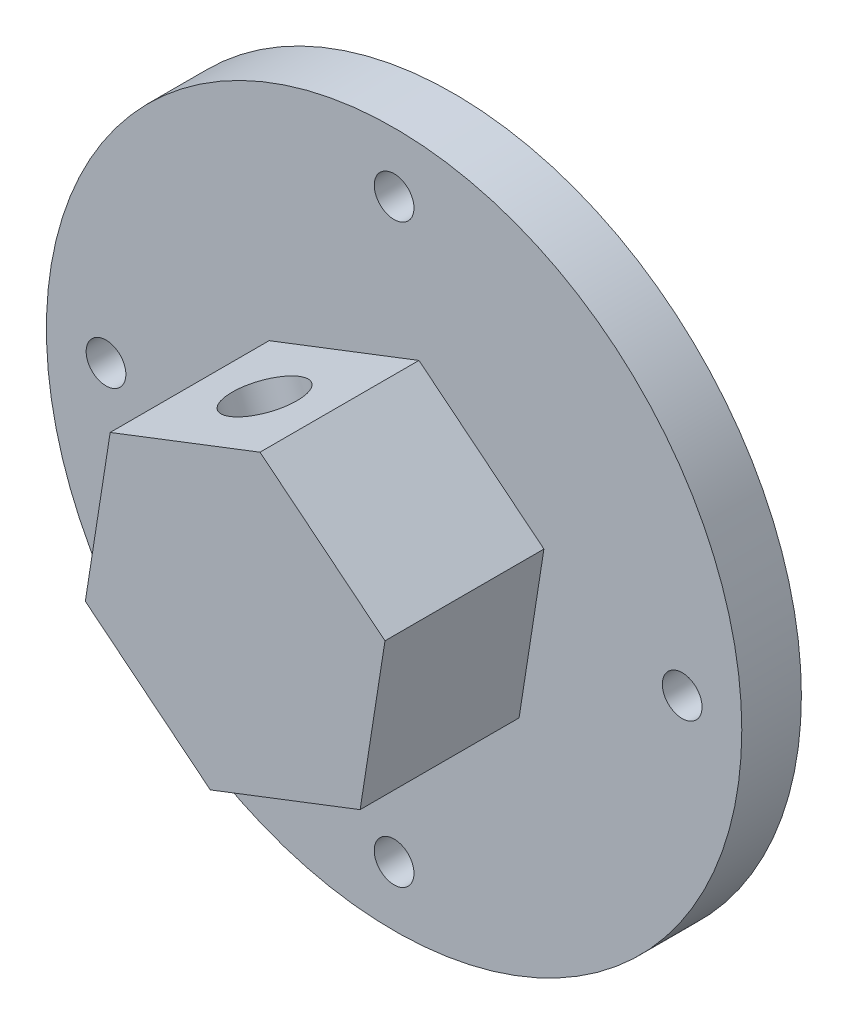
SolidWorks part; units mm, degrees
ref_plane "Alzado" through (0, 0, 0) normal (0, 0, 1) x (1, 0, 0)
ref_plane "Planta" through (0, 0, 0) normal (0, 1, 0) x (1, 0, 0)
ref_plane "Vista lateral" through (0, 0, 0) normal (1, 0, 0) x (0, 0, -1)
sketch "Croquis1" plane through (0, 0, 0) normal (0, 0, 1) x (1, 0, 0)
  circle A0 centre (0, 0) radius 17.5
  circle A1 centre (0, 0) radius 14.5 construction
  circle A2 centre (0, 14.5) radius 1
  circle A3 centre (14.5, 0) radius 1
  circle A4 centre (0, -14.5) radius 1
  circle A5 centre (-14.5, 0) radius 1
  point P15 (0, 0)
  dimension "D1" = 35
  dimension "D2" = 29
  dimension "D3" = 2
  dimension "D4" = 4
extrude "Saliente-Extruir1" add sketch "Croquis1" along normal blind 3
sketch "Croquis2" plane through (0, 0, 3) normal (0, 0, 1) x (1, 0, 0)
  line L1 (1.2508, 7.9855) -> (-6.2903, 5.076)
  line L2 (-6.2903, 5.076) -> (-7.5411, -2.9096)
  line L3 (-7.5411, -2.9096) -> (-1.2508, -7.9855)
  line L4 (-1.2508, -7.9855) -> (6.2903, -5.076)
  line L5 (6.2903, -5.076) -> (7.5411, 2.9096)
  line L6 (7.5411, 2.9096) -> (1.2508, 7.9855)
  circle A0 centre (0, 0) radius 7 construction
  circle A1 centre (0, 14.5) radius 2.1 construction
  circle A2 centre (9.5, 0) radius 2.1 construction
  circle A3 centre (-5, -9.5) radius 2.1 construction
  circle A4 centre (-14.5, 5) radius 2.1 construction
  point P12 (1.5597, 9.9577)
  point P21 (-2.5, 2.5)
  dimension "D1" = 4.2
  dimension "D3" = 14
  dimension "D2" = 4
extrude "Saliente-Extruir2" add sketch "Croquis2" along normal blind 8
sketch "Croquis3" plane through (2.5197, -6.5308, 0) normal (0.36, -0.933, 0) x (0.933, 0.36, 0)
  circle A0 centre (0, 7) radius 1.75
extrude "Cortar-Extruir1" cut sketch "Croquis3" against normal up to next
